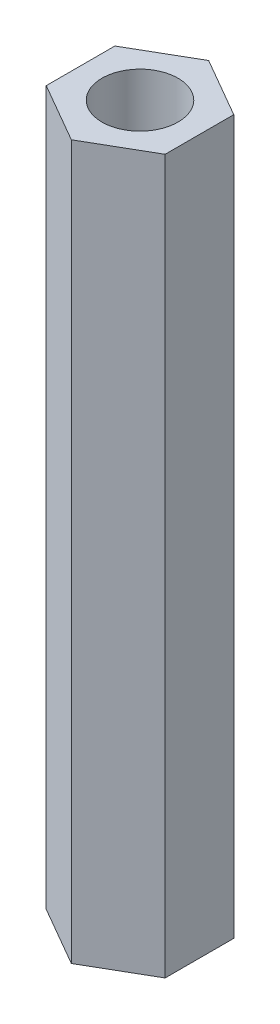
SolidWorks part; units mm, degrees
ref_plane "前视基准面" through (0, 0, 0) normal (0, 0, 1) x (1, 0, 0)
ref_plane "上视基准面" through (0, 0, 0) normal (0, 1, 0) x (1, 0, 0)
ref_plane "右视基准面" through (0, 0, 0) normal (1, 0, 0) x (0, 0, -1)
other "Configuration Table"
sketch "草图1" plane through (0, 0, 0) normal (0, 1, 0) x (1, 0, 0)
  line L1 (0, 2.8868) -> (-2.5, 1.4434)
  line L2 (-2.5, 1.4434) -> (-2.5, -1.4434)
  line L3 (-2.5, -1.4434) -> (0, -2.8868)
  line L4 (0, -2.8868) -> (2.5, -1.4434)
  line L5 (2.5, -1.4434) -> (2.5, 1.4434)
  line L6 (2.5, 1.4434) -> (0, 2.8868)
  circle A0 centre (0, 0) radius 2.5 construction
  circle A1 centre (0, 0) radius 1.6
  dimension "D1" = 3.2
  dimension "D2" = 5
extrude "凸台-拉伸1" add sketch "草图1" along normal blind 30
